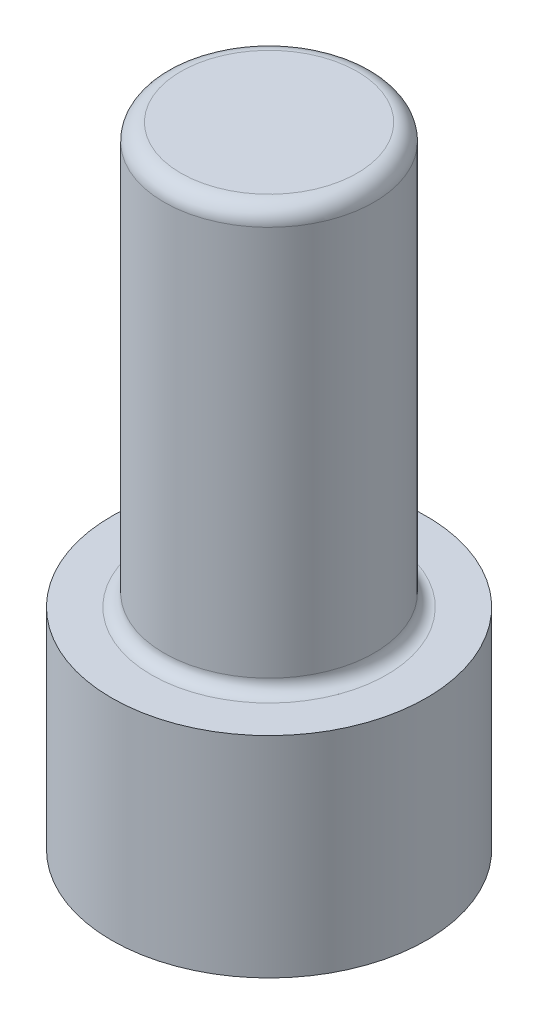
SolidWorks part; units mm, degrees
ref_plane "Front Plane" through (0, 0, 0) normal (0, 0, 1) x (1, 0, 0)
ref_plane "Top Plane" through (0, 0, 0) normal (0, 1, 0) x (1, 0, 0)
ref_plane "Right Plane" through (0, 0, 0) normal (1, 0, 0) x (0, 0, -1)
sketch "Sketch1" plane through (0, 0, 0) normal (0, 1, 0) x (1, 0, 0)
  circle A0 centre (0, 0) radius 187.5
extrude "Boss-Extrude1" add sketch "Sketch1" along normal blind 250 contours A0
sketch "Sketch2" plane through (0, 250, 0) normal (0, 1, 0) x (1, 0, 0)
  circle A0 centre (0, 0) radius 125
extrude "Boss-Extrude2" add sketch "Sketch2" along normal blind 500
fillet "Fillet1" radius 15 1 edges at (0, 250, 125)
fillet "Fillet2" radius 20 1 edges at (0, 750, 125)
sketch "Sketch3" plane through (0, 0, 0) normal (0, -1, 0) x (-1, 0, 0)
  line L1 (97.2142, -31.62) -> (75.9908, 68.38)
  line L2 (75.9908, 68.38) -> (-21.2234, 100)
  line L3 (-21.2234, 100) -> (-97.2142, 31.62)
  line L4 (-97.2142, 31.62) -> (-75.9908, -68.38)
  line L5 (-75.9908, -68.38) -> (21.2234, -100)
  line L6 (21.2234, -100) -> (97.2142, -31.62)
  circle A0 centre (0, 0) radius 88.5315 construction
  dimension "D1" = 200
extrude "Cut-Extrude1" cut sketch "Sketch3" against normal blind 150
